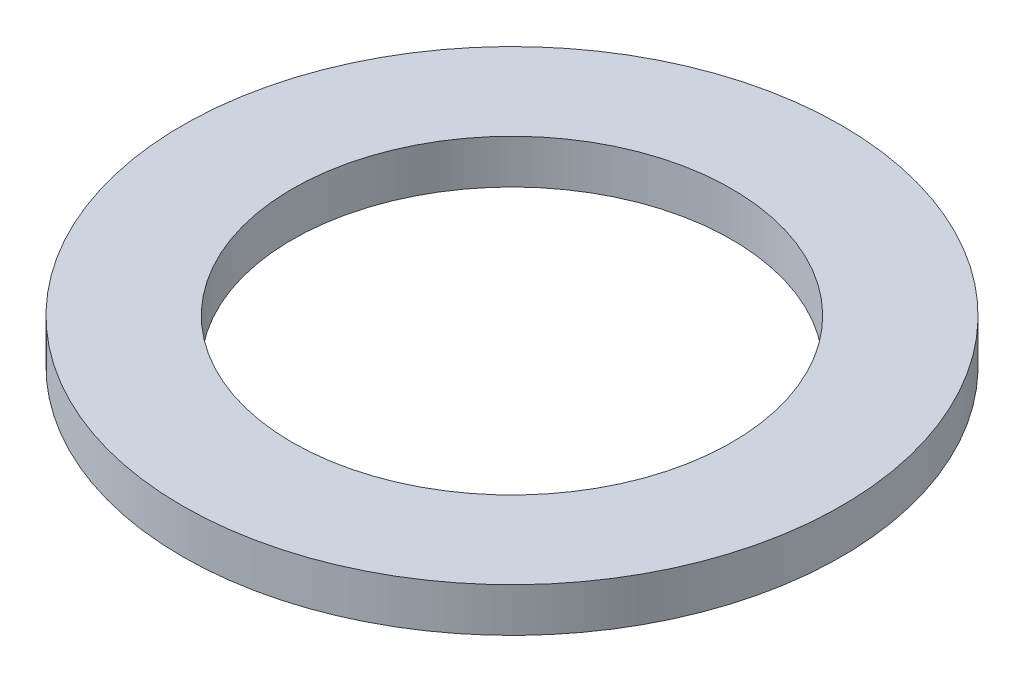
SolidWorks part; units mm, degrees
ref_plane "前视基准面" through (0, 0, 0) normal (0, 0, 1) x (1, 0, 0)
ref_plane "上视基准面" through (0, 0, 0) normal (0, 1, 0) x (1, 0, 0)
ref_plane "右视基准面" through (0, 0, 0) normal (1, 0, 0) x (0, 0, -1)
other "Configuration Table"
sketch "草图1" plane through (0, 0, 0) normal (0, 1, 0) x (1, 0, 0)
  circle A0 centre (0, 0) radius 5
  circle A1 centre (0, 0) radius 7.5
  dimension "D1" = 10
  dimension "D2" = 15
extrude "凸台-拉伸1" add sketch "草图1" along normal blind 1
